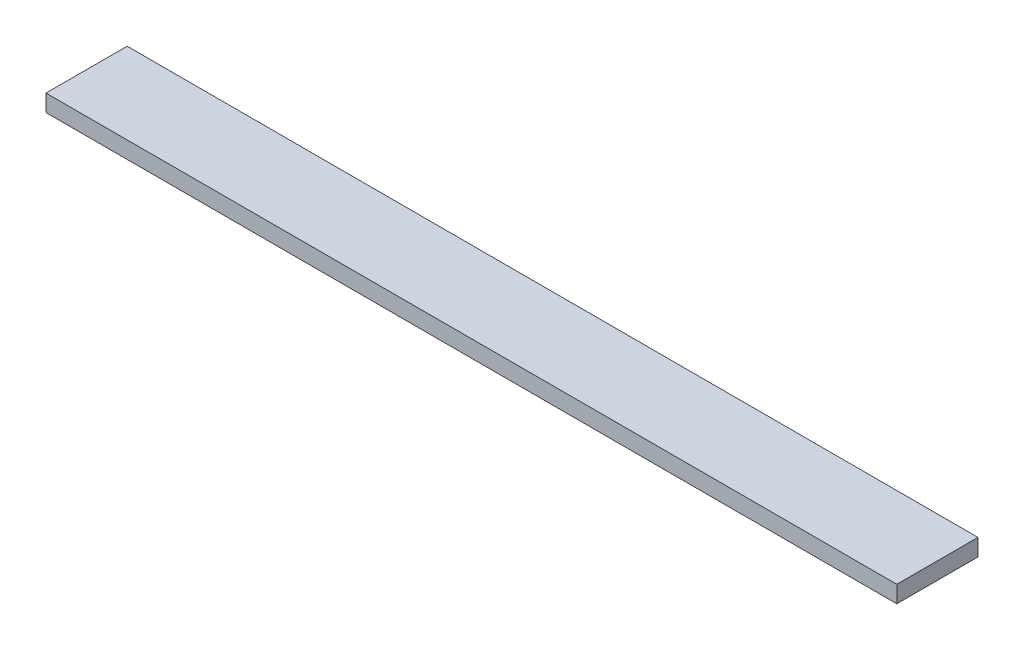
SolidWorks part; units mm, degrees
ref_plane "Front Plane" through (0, 0, 0) normal (0, 0, 1) x (1, 0, 0)
ref_plane "Top Plane" through (0, 0, 0) normal (0, 1, 0) x (1, 0, 0)
ref_plane "Right Plane" through (0, 0, 0) normal (1, 0, 0) x (0, 0, -1)
sketch "Sketch1" plane through (0, 0, 0) normal (1, 0, 0) x (0, 0, -1)
  line L1 (0, 0) -> (48, 0)
  line L2 (0, 0) -> (0, 10)
  line L3 (0, 10) -> (48, 10)
  line L4 (48, 0) -> (48, 10)
  dimension "D1" = 48
  dimension "D2" = 10
extrude "Boss-Extrude1" add sketch "Sketch1" along normal blind 503
ref_plane "Plane1" through (0, 0, -24) normal (0, 0, 1) x (1, 0, 0)
ref_plane "Plane2" through (251.5, 0, 0) normal (-1, 0, 0) x (0, 0, 1)
